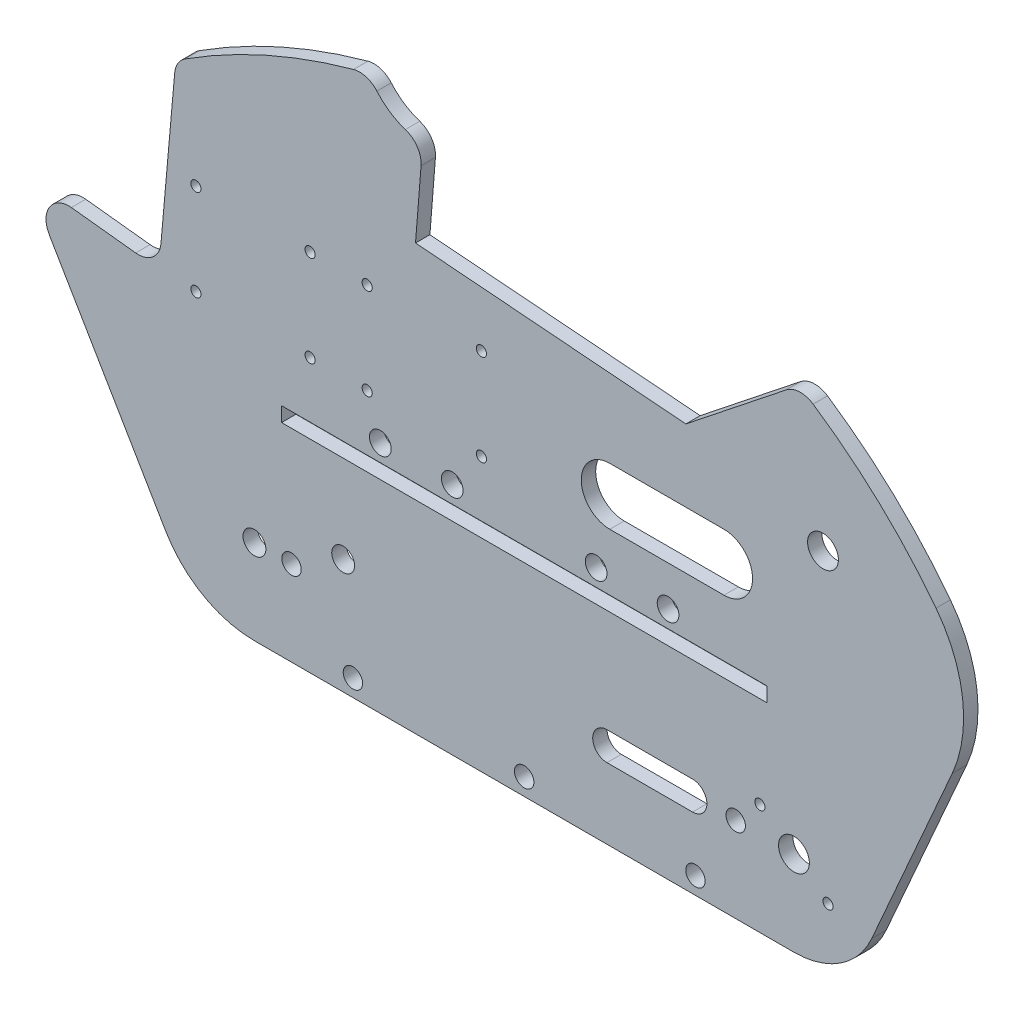
SolidWorks part; units mm, degrees
ref_plane "Front Plane" through (0, 0, 0) normal (0, 0, 1) x (1, 0, 0)
ref_plane "Top Plane" through (0, 0, 0) normal (0, 1, 0) x (1, 0, 0)
ref_plane "Right Plane" through (0, 0, 0) normal (1, 0, 0) x (0, 0, -1)
sketch "Sketch1" plane through (0, 0, 0) normal (0, 0, 1) x (1, 0, 0)
  line L8 (0, 18.9078) -> (120.015, 18.9078) construction
  line L18 (155.2575, 52.1157) -> (-35.2425, 52.1157) construction
  line L37 (0, 0) -> (120.015, 0)
  line L42 (19.7347, 25.5664) -> (0, 18.9078) construction
  line L54 (155.2575, 52.1157) -> (137.3256, 11.3022)
  line L55 (60.0075, 52.1157) -> (60.0075, 18.9078) construction
  line L56 (-35.2425, 52.1157) -> (-17.3106, 11.3022)
  line L59 (151.631, 82.096) -> (-31.616, 82.096) construction
  circle A21 centre (120.015, 18.9078) radius 3.429
  circle A22 centre (0, 18.9078) radius 2.54
  circle A24 centre (19.7347, 25.5664) radius 2.54
  arc A25 (137.3256, 11.3022) -> (120.015, 0) centre (120.015, 18.9078) cw
  arc A26 (0, 0) -> (-17.3106, 11.3022) centre (0, 18.9078) cw
  arc A28 (151.631, 82.096) -> (-31.616, 82.096) centre (60.0075, 11.7572) ccw
  arc A29 (151.631, 82.096) -> (155.2575, 52.1157) centre (128.1135, 64.0417) cw
  arc A30 (-31.616, 82.096) -> (-35.2425, 52.1157) centre (-8.0985, 64.0417) ccw
  dimension "D5" = 18.9078
  dimension "D8" = 29.9803
  dimension "D3" = 52.1157
  dimension "D2" = 6.858
  dimension "D10" = 5.08
  dimension "D1" = 190.5
  dimension "D4" = 18.645
  dimension "D6" = 20.8278
  dimension "D7" = 120.015
  dimension "D9" = 183.2469
extrude "Boss-Extrude1" add sketch "Sketch1" along normal blind 3.2004
sketch "Sketch2" plane through (0, 0, 0) normal (0, 0, -1) x (-1, 0, 0)
  line L14 (-155.2575, 52.1157) -> (35.2425, 52.1157) construction
  line L28 (-92.0115, 52.1157) -> (-76.0095, 52.1157) construction
  line L29 (-76.0095, 52.1157) -> (-44.0055, 52.1157) construction
  line L30 (-44.0055, 52.1157) -> (-28.0035, 52.1157) construction
  circle A0 centre (-92.0115, 52.1157) radius 2.413
  circle A1 centre (-76.0095, 52.1157) radius 2.413
  circle A2 centre (-44.0055, 52.1157) radius 2.413
  circle A3 centre (-28.0035, 52.1157) radius 2.413
  point P11 (-36.0045, 52.1157)
  point P16 (-84.0105, 52.1157)
  dimension "D3" = 4.826
  dimension "D2" = 16.002
  dimension "D4" = 48.006
extrude "Cut-Extrude1" cut sketch "Sketch2" against normal blind 3.2004
sketch "Sketch3" plane through (0, 0, 3.2004) normal (0, 0, 1) x (1, 0, 0)
  line L0 (60.0075, 7.62) -> (60.0075, 0) construction
  line L1 (21.9075, 3.81) -> (98.1075, 3.81) construction
  line L2 (0, 0) -> (120.015, 0) construction
  circle A0 centre (21.9075, 3.81) radius 2.159
  circle A1 centre (60.0075, 3.81) radius 2.159
  circle A2 centre (98.1075, 3.81) radius 2.159
  point P6 (60.0075, 3.81)
  dimension "D3" = 4.318
  dimension "D1" = 76.2
  dimension "D2" = 7.62
extrude "Cut-Extrude2" cut sketch "Sketch3" against normal up to surface (3.2004 mm away) up to face at (89.5985, 52.1157, 0)
sketch "Sketch5" plane through (0, 0, 0) normal (0, 0, -1) x (-1, 0, 0)
  line L0 (-60.0075, 52.1157) -> (-60.0075, 0) construction
  line L1 (-76.0095, 52.1157) -> (-44.0055, 52.1157) construction
  line L3 (0, 0) -> (-120.015, 0) construction
sketch "Sketch6" plane through (0, 0, 0) normal (0, 0, -1) x (-1, 0, 0)
  line L0 (-155.2575, 52.1157) -> (35.2425, 52.1157) construction
  line L1 (-113.9825, 81.3257) -> (-6.0325, 81.3257) construction
  line L2 (-113.9825, 81.3257) -> (-113.9825, 55.9257) construction
  line L3 (-113.9825, 55.9257) -> (-6.0325, 55.9257) construction
  line L4 (-6.0325, 81.3257) -> (-6.0325, 55.9257) construction
  line L5 (-60.0075, 52.1157) -> (-60.0075, 18.9078) construction
  line L6 (-60.0075, 55.9257) -> (-60.0075, 52.1157) construction
  line L7 (-60.0075, 52.1157) -> (-60.0075, 48.3057) construction
  line L9 (-6.0325, 48.3057) -> (-113.9825, 48.3057)
  line L10 (-6.0325, 48.3057) -> (-6.0325, 45.0545)
  line L11 (-6.0325, 45.0545) -> (-113.9825, 45.0545)
  line L12 (-113.9825, 48.3057) -> (-113.9825, 45.0545)
  dimension "D1" = 25.4
  dimension "D2" = 107.95
  dimension "D3" = 3.81
  dimension "D4" = 7.62
  dimension "D5" = 3.2512
extrude "Cut-Extrude3" cut sketch "Sketch6" against normal up to surface (3.2004 mm away) up to face at (24.0665, 3.81, 3.2004)
sketch "Sketch7" plane through (0, 0, 3.2004) normal (0, 0, 1) x (1, 0, 0)
  line L0 (146.2916, 31.7089) -> (111.6995, 46.9073) construction
  line L1 (111.6995, 46.9073) -> (126.4745, 80.5358) construction
  line L3 (137.3256, 11.3022) -> (155.2575, 52.1157) construction
  circle A0 centre (126.4745, 80.5358) radius 3.429
  circle A3 centre (120.015, 18.9078) radius 3.429 construction
  dimension "D1" = 37.7837
  dimension "D2" = 36.7311
extrude "Cut-Extrude4" cut sketch "Sketch7" against normal up to surface (3.2004 mm away) up to face at (60.0075, 46.6801, 0)
sketch "Sketch8" plane through (0, 0, 3.2004) normal (0, 0, 1) x (1, 0, 0)
  line L0 (-32.6149, 80.7753) -> (-17.2714, 56.9367)
  line L1 (-17.2714, 56.9367) -> (38.7942, 93.0228)
  line L2 (38.7942, 93.0228) -> (47.3024, 126.5656)
  line L3 (0, 18.9078) -> (0, 56.9367) construction
  line L4 (0, 56.9367) -> (-17.2714, 56.9367) construction
  line L5 (0, 0) -> (120.015, 0) construction
  arc A0 (151.631, 82.096) -> (-31.616, 82.096) centre (60.0075, 11.7572) ccw construction
  arc A1 (47.3024, 126.5656) -> (-32.6149, 80.7753) centre (60.0075, 11.7572) ccw
  circle A2 centre (0, 18.9078) radius 2.54 construction
  dimension "D1" = 66.675
  dimension "D2" = 137
  dimension "D3" = 28.3497
  dimension "D4" = 38.0289
  dimension "D5" = 17.2714
sketch "Sketch9" plane through (0, 0, 3.2004) normal (0, 0, 1) x (1, 0, 0)
  line L1 (-37.7469, 127.2665) -> (113.9825, 127.2665)
  line L2 (-37.7469, 127.2665) -> (-37.7469, 55.9257)
  line L3 (-37.7469, 55.9257) -> (113.9825, 55.9257)
  line L4 (113.9825, 127.2665) -> (113.9825, 55.9257)
  line L6 (113.9825, 81.3257) -> (113.9825, 55.9257) construction
  line L7 (113.9825, 55.9257) -> (6.0325, 55.9257) construction
  arc A0 (151.631, 82.096) -> (-31.616, 82.096) centre (60.0075, 11.7572) ccw construction
  arc A1 (-31.616, 82.096) -> (-35.2425, 52.1157) centre (-8.0985, 64.0417) ccw construction
sketch "Sketch11" plane through (0, 0, 3.2004) normal (0, 0, 1) x (1, 0, 0)
  line L0 (121.1584, 109.7519) -> (95.9667, 89.7527)
  line L1 (95.9667, 89.7527) -> (35.8322, 94.543)
  line L2 (35.8322, 94.543) -> (38.2746, 125.2036)
  line L3 (113.9825, 48.3057) -> (6.0325, 48.3057) construction
  arc A0 (151.631, 82.096) -> (-31.616, 82.096) centre (60.0075, 11.7572) ccw construction
  arc A1 (38.2746, 125.2036) -> (121.1584, 109.7519) centre (60.0075, 11.7572) cw
  dimension "D1" = 60.325
  dimension "D2" = 137
  dimension "D3" = 4.555
  dimension "D4" = 30.7577
  dimension "D5" = 32.1651
extrude "Cut-Extrude5" cut sketch "Sketch11" against normal up to surface (3.2004 mm away) up to face at (123.0455, 80.5358, 0)
sketch "Sketch12" plane through (0, 0, 3.2004) normal (0, 0, 1) x (1, 0, 0)
  line L2 (36.8571, 114.619) -> (37.4279, 114.5735)
  line L3 (38.2746, 125.2036) -> (35.8322, 94.543) construction
  line L4 (38.2746, 125.2036) -> (37.4279, 114.5735)
  arc A0 (25.5198, 121.9978) -> (36.8571, 114.619) centre (37.9826, 128.7474) ccw
  arc A2 (38.2746, 125.2036) -> (-31.616, 82.096) centre (60.0075, 11.7572) ccw construction
  arc A3 (25.5198, 121.9978) -> (38.2746, 125.2036) centre (60.0075, 11.7572) cw
  dimension "D1" = 0.5725
  dimension "D3" = 14.1732
  dimension "D2" = 10.6637
extrude "Cut-Extrude6" cut sketch "Sketch12" against normal up to surface (3.2004 mm away) up to face at (64.0478, 59.4924, 0)
sketch "Sketch14" plane through (0, 0, 3.2004) normal (0, 0, 1) x (1, 0, 0)
  line L0 (-45.1695, 54.5744) -> (-19.7801, 11.3248)
  line L1 (0, 0) -> (120.015, 0) construction
  line L2 (-42.2178, 81.9333) -> (25.5198, 121.9978) construction
  line L3 (-42.2178, 81.9333) -> (-45.1695, 54.5744) construction
  line L4 (-9.8103, 145.4597) -> (-9.8103, -20.3847) construction
  arc A0 (25.5198, 121.9978) -> (-42.2178, 81.9333) centre (58.563, -11.1634) ccw
  arc A1 (-42.2178, 81.9333) -> (-45.1695, 54.5744) centre (-25.2559, 66.2646) ccw
  arc A4 (-19.7801, 11.3248) -> (0, 0) centre (0, 22.9366) ccw
  arc A5 (25.5198, 121.9978) -> (0, 0) centre (72.933, 48.4118) ccw
  dimension "D2" = 137.1997
  dimension "D4" = 87.5381
  dimension "D5" = 23.0914
  dimension "D1" = 30.415
  dimension "D3" = 78.6991
  dimension "D6" = 27.5176
extrude "Boss-Extrude2" add sketch "Sketch14" against normal up to surface (3.2004 mm away) up to face at (59.289, 66.8891, 0)
sketch "Sketch13" plane through (0, 0, 3.2004) normal (0, 0, 1) x (1, 0, 0)
  line L0 (50.4825, 81.0717) -> (50.4825, 60.7517) construction
  line L5 (25.0825, 81.0717) -> (25.0825, 60.7517) construction
  line L6 (50.4825, 70.9117) -> (25.0825, 70.9117) construction
  line L7 (12.3825, 81.0717) -> (12.3825, 60.7517) construction
  line L8 (-13.0175, 81.0717) -> (-13.0175, 60.7517) construction
  line L9 (12.3825, 70.9117) -> (-13.0175, 70.9117) construction
  line L10 (113.9825, 48.3057) -> (6.0325, 48.3057) construction
  line L11 (113.9825, 45.0545) -> (113.9825, 48.3057) construction
  circle A0 centre (50.4825, 81.0717) radius 1.1303
  circle A1 centre (50.4825, 60.7517) radius 1.1303
  circle A2 centre (25.0825, 60.7517) radius 1.1303
  circle A3 centre (25.0825, 81.0717) radius 1.1303
  circle A4 centre (12.3825, 81.0717) radius 1.1303
  circle A5 centre (12.3825, 60.7517) radius 1.1303
  circle A6 centre (-13.0175, 60.7517) radius 1.1303
  circle A7 centre (-13.0175, 81.0717) radius 1.1303
  point P13 (37.7825, 70.9117)
  point P22 (-0.3175, 70.9117)
  dimension "D5" = 2.2606
  dimension "D1" = 63.5
  dimension "D2" = 12.7
  dimension "D3" = 25.4
  dimension "D4" = 20.32
  dimension "D6" = 22.606
extrude "Cut-Extrude7" cut sketch "Sketch13" against normal up to surface (3.2004 mm away) up to face at (57.6394, 67.0894, 0)
sketch "Sketch15" plane through (0, 0, 3.2004) normal (0, 0, 1) x (1, 0, 0)
  line L0 (113.9825, 48.3057) -> (6.0325, 48.3057) construction
  line L1 (79.0575, 73.7057) -> (104.4575, 73.7057)
  line L2 (79.0575, 73.7057) -> (79.0575, 61.0057) construction
  line L3 (79.0575, 61.0057) -> (104.4575, 61.0057)
  line L4 (104.4575, 73.7057) -> (104.4575, 61.0057) construction
  line L5 (113.9825, 45.0545) -> (113.9825, 48.3057) construction
  line L6 (78.4225, 22.0828) -> (97.4725, 22.0828)
  line L7 (78.4225, 22.0828) -> (78.4225, 15.7328) construction
  line L8 (78.4225, 15.7328) -> (97.4725, 15.7328)
  line L9 (97.4725, 22.0828) -> (97.4725, 15.7328) construction
  line L10 (6.0325, 45.0545) -> (113.9825, 45.0545) construction
  line L11 (97.4725, 18.9078) -> (120.015, 18.9078) construction
  line L12 (0, 0) -> (120.015, 0) construction
  arc A0 (104.4575, 73.7057) -> (104.4575, 61.0057) centre (104.4575, 67.3557) cw
  arc A1 (79.0575, 73.7057) -> (79.0575, 61.0057) centre (79.0575, 67.3557) ccw
  arc A2 (97.4725, 22.0828) -> (97.4725, 15.7328) centre (97.4725, 18.9078) cw
  arc A3 (78.4225, 22.0828) -> (78.4225, 15.7328) centre (78.4225, 18.9078) ccw
  circle A4 centre (120.015, 18.9078) radius 3.429 construction
  circle A5 centre (92.0115, 52.1157) radius 2.413 construction
  dimension "D4" = 8.89
  dimension "D1" = 25.4
  dimension "D2" = 12.7
  dimension "D3" = 12.446
  dimension "D5" = 6.35
  dimension "D6" = 19.05
  dimension "D7" = 16.51
extrude "Cut-Extrude8" cut sketch "Sketch15" against normal up to surface (3.2004 mm away) up to face at (49.3522, 60.7517, 0)
fillet "Fillet1" radius 5.08 3 edges at (121.1584, 109.7519, 1.6002) (37.4279, 114.5735, 1.6002) (25.5198, 121.9978, 1.6002)
sketch "Sketch16" plane through (0, 0, 3.2004) normal (0, 0, 1) x (1, 0, 0)
  line L0 (112.4381, 24.6798) -> (127.5919, 13.1357) construction
  line L1 (0, 0) -> (120.015, 0) construction
  circle A0 centre (112.4381, 24.6798) radius 1.1303
  circle A1 centre (127.5919, 13.1357) radius 1.1303
  circle A4 centre (120.015, 18.9078) radius 3.429 construction
  point P10 (120.015, 18.9078)
  dimension "D1" = 2.2606
  dimension "D2" = 37.3
  dimension "D3" = 19.05
extrude "Cut-Extrude9" cut sketch "Sketch16" against normal up to surface (3.2004 mm away) up to face at (87.9475, 18.9078, 0)
sketch "Sketch20" plane through (0, 0, 3.2004) normal (0, 0, 1) x (1, 0, 0)
  line L0 (8.255, 18.9078) -> (107.0559, 18.9078) construction
  line L1 (60.0075, 18.9078) -> (60.0075, 0) construction
  line L3 (0, 0) -> (120.015, 0) construction
  circle A0 centre (8.255, 18.9078) radius 2.159
  circle A1 centre (107.0559, 18.9078) radius 2.159
  dimension "D1" = 4.318
  dimension "D3" = 47.0484
  dimension "D2" = 51.7525
  dimension "D4" = 18.9078
extrude "Cut-Extrude11" cut sketch "Sketch20" against normal up to surface (3.2004 mm away) up to face at (111.3078, 24.6798, 0)
sketch "Sketch21" plane through (0, 0, 0) normal (0, 0, -1) x (-1, 0, 0)
  line L0 (16.7316, 111.864) -> (21.2549, 60.9334)
  line L1 (21.2549, 60.9334) -> (65.1052, 65.8156)
  line L2 (65.1052, 65.8156) -> (16.7316, 111.864)
  line L4 (13.0175, 81.0717) -> (13.0175, 60.7517) construction
  line L6 (17.9749, 60.5682) -> (40.4813, 63.074) construction
  dimension "D1" = 5.075
extrude "Cut-Extrude12" cut sketch "Sketch21" against normal up to surface (3.2004 mm away) up to face at (10.414, 18.9078, 3.2004)
fillet "Fillet2" radius 5.08 3 edges at (-48.2297, 63.9367, 1.6002) (-17.518, 103.0095, 1.6002) (-21.2549, 60.9334, 1.6002)
